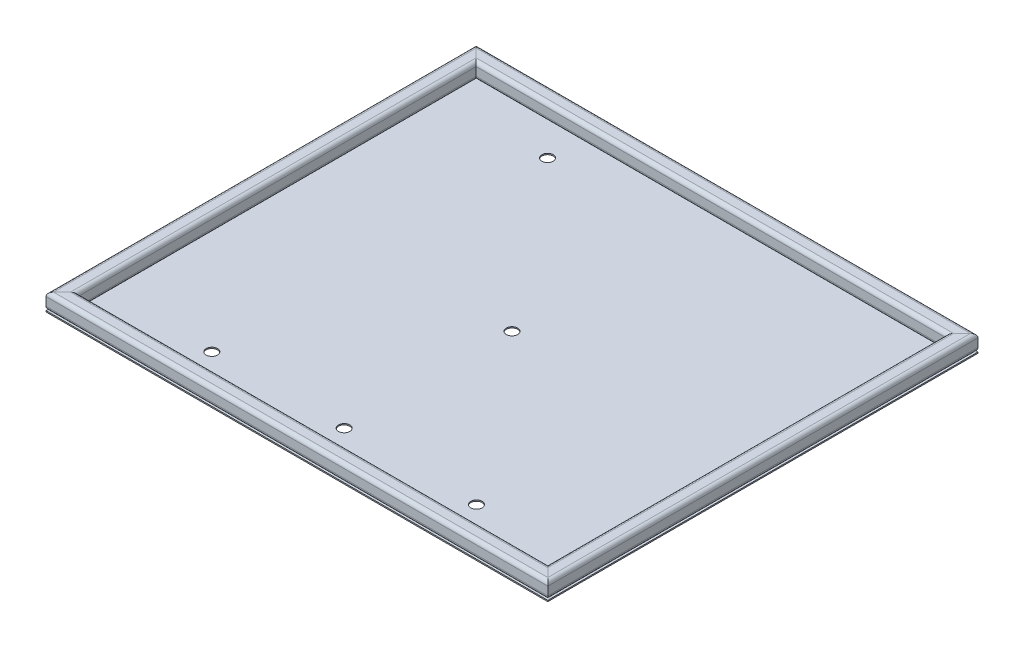
SolidWorks part; units mm, degrees
ref_plane "Alzado" through (0, 0, 0) normal (0, 0, 1) x (1, 0, 0)
ref_plane "Planta" through (0, 0, 0) normal (0, 1, 0) x (1, 0, 0)
ref_plane "Vista lateral" through (0, 0, 0) normal (1, 0, 0) x (0, 0, -1)
sketch "Croquis1" plane through (0, 0, 0) normal (0, 1, 0) x (1, 0, 0)
  line L1 (-398.2, 341.4) -> (398.2, 341.4)
  line L2 (-398.2, 341.4) -> (-398.2, -341.4)
  line L3 (-398.2, -341.4) -> (398.2, -341.4)
  line L4 (398.2, 341.4) -> (398.2, -341.4)
  line L5 (-398.2, 341.4) -> (398.2, -341.4) construction
  line L6 (-398.2, -341.4) -> (398.2, 341.4) construction
  point P0 (0, 0)
  dimension "D1" = 682.8
  dimension "D2" = 796.4
other "Tubo cuadrado 2 X 2 X 0.25(1)"
ref_plane "Plano1" through (-385.5, 12.7, -341.4) normal (0, 0, 1) x (1, 0, 0)
sketch "Sketch1" plane through (-385.5, 12.7, -341.4) normal (0, 0, 1) x (1, 0, 0)
  line L0 (-6.7, -9.7) -> (6.7, -9.7)
  line L1 (-9.7, -6.7) -> (-9.7, 6.7)
  line L2 (6.7, 9.7) -> (-6.7, 9.7)
  line L3 (9.7, 6.7) -> (9.7, -6.7)
  line L4 (-6.7, -12.7) -> (6.7, -12.7)
  line L5 (-12.7, -6.7) -> (-12.7, 6.7)
  line L6 (6.7, 12.7) -> (-6.7, 12.7)
  line L7 (12.7, 6.7) -> (12.7, -6.7)
  line L8 (0, 0) -> (9.7, 0) construction
  line L9 (0, 0) -> (0, 9.7) construction
  arc A0 (12.7, 6.7) -> (6.7, 12.7) centre (6.7, 6.7) ccw
  arc A1 (6.7, -12.7) -> (12.7, -6.7) centre (6.7, -6.7) ccw
  arc A2 (-12.7, -6.7) -> (-6.7, -12.7) centre (-6.7, -6.7) ccw
  arc A3 (-6.7, 12.7) -> (-12.7, 6.7) centre (-6.7, 6.7) ccw
  arc A4 (-6.7, 9.7) -> (-9.7, 6.7) centre (-6.7, 6.7) ccw
  arc A5 (9.7, 6.7) -> (6.7, 9.7) centre (6.7, 6.7) ccw
  arc A6 (6.7, -9.7) -> (9.7, -6.7) centre (6.7, -6.7) ccw
  arc A7 (-9.7, -6.7) -> (-6.7, -9.7) centre (-6.7, -6.7) ccw
  point P3 (0, 12.7)
  point P4 (12.7, 0)
  point P5 (0, -12.7)
  point P6 (-12.7, 0)
  point P7 (-12.7, 12.7)
  point P8 (-12.7, -12.7)
  point P33 (0, 0)
  point P35 (12.7, -12.7)
  point P36 (12.7, 12.7)
  point P37 (0, 0)
  dimension "D1" = 6
  dimension "Thickness" = 3
  dimension "V_leg" = 25.4
sketch "Croquis3" plane through (0, 0, 0) normal (0, -1, 0) x (1, 0, 0)
  line L1 (398.2, 341.4) -> (-398.2, 341.4)
  line L2 (398.2, 341.4) -> (398.2, -341.4)
  line L3 (398.2, -341.4) -> (-398.2, -341.4)
  line L4 (-398.2, 341.4) -> (-398.2, -341.4)
  line L5 (398.2, 341.4) -> (-398.2, -341.4) construction
  line L6 (398.2, -341.4) -> (-398.2, 341.4) construction
  point P0 (0, 0)
extrude "Saliente-Extruir1" add sketch "Croquis3" along normal blind 1.9 separate body
ref_plane "Plano2" through (0, 0, 266.4) normal (0, 0, 1) x (1, 0, 0)
sketch "Croquis4" plane through (0, -1128.704, 0) normal (0, 1, 0) x (1, 0, 0)
  circle A0 centre (2010, 436.4137) radius 8.0354
sketch "Croquis5" plane through (0, 0, 0) normal (0, 1, 0) x (1, 0, 0)
  circle A0 centre (233, -210.2449) radius 3.1562
  circle A1 centre (210, -210) radius 7.8426
  circle A2 centre (187, -209.7551) radius 3.1812
  circle A3 centre (0, -210) radius 7.9375
  circle A4 centre (-23, -209.7551) radius 3.175
  circle A5 centre (23, -210.2449) radius 3.244
  circle A6 centre (-233, -209.7551) radius 3.175
  circle A7 centre (-210, -210) radius 7.9375
  circle A8 centre (-187, -210.2449) radius 3.175
sketch "Croquis6" plane through (0, -1.9, 0) normal (0, -1, 0) x (1, 0, 0)
  line L0 (-398.2, -266.4) -> (-210, -266.4) construction
  line L1 (-398.2, 341.4) -> (-398.2, -341.4) construction
  line L2 (-210, -266.4) -> (-210, -341.4) construction
  line L3 (-398.2, -341.4) -> (398.2, -341.4) construction
  line L4 (-398.2, 266.4) -> (-210, 266.4) construction
  line L5 (-398.2, 341.4) -> (-398.2, -341.4) construction
  line L6 (-210, 266.4) -> (-210, 341.4) construction
  line L7 (398.2, 341.4) -> (-398.2, 341.4) construction
  line L8 (-210, 266.4) -> (0, 266.4) construction
  line L9 (0, 266.4) -> (210, 266.4) construction
  circle A0 centre (0, 0) radius 9
  circle A1 centre (210, 266.4) radius 9
  circle A2 centre (0, 266.4) radius 9
  circle A3 centre (-210, 266.4) radius 9
  circle A4 centre (-210, -266.4) radius 9
  dimension "D7" = 18
  dimension "D8" = 18
  dimension "D9" = 18
  dimension "D10" = 18
  dimension "D11" = 18
  dimension "D1" = 75
  dimension "D2" = 188.2
  dimension "D3" = 188.2
  dimension "D4" = 75
  dimension "D5" = 210
  dimension "D6" = 210
extrude "Cortar-Extruir2" cut sketch "Croquis6" against normal blind 10
sketch "Croquis7" plane through (0, -1.9, 0) normal (0, -1, 0) x (1, 0, 0)
  line L0 (9, 266.4) -> (0, 266.4) construction
  line L1 (0, 266.4) -> (0, 0) construction
  circle A0 centre (0, 266.4) radius 9 construction
